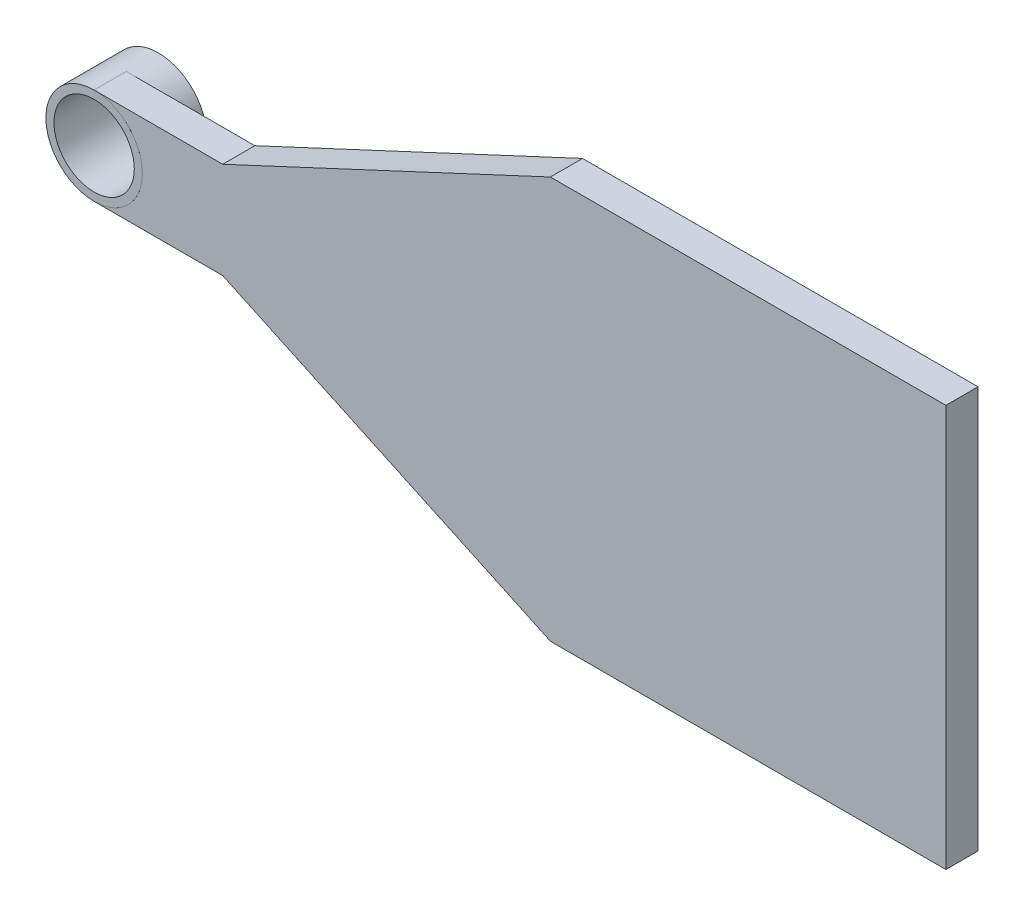
SolidWorks part; units mm, degrees
ref_plane "Front Plane" through (0, 0, 0) normal (0, 0, 1) x (1, 0, 0)
ref_plane "Top Plane" through (0, 0, 0) normal (0, 1, 0) x (1, 0, 0)
ref_plane "Right Plane" through (0, 0, 0) normal (1, 0, 0) x (0, 0, -1)
sketch "Sketch2" plane through (0, 0, 0) normal (0, 0, 1) x (1, 0, 0)
  circle A0 centre (0, 0) radius 5
  circle A1 centre (0, 0) radius 6
  dimension "D1" = 10
extrude "Boss-Extrude1" add sketch "Sketch2" along normal blind 8
ref_plane "Plane1" through (6, 0, 0) normal (1, 0, 0) x (0, 0, -1)
sketch "Sketch3" plane through (6, 0, 0) normal (1, 0, 0) x (0, 0, -1)
  line L0 (-8, 6) -> (-8, -6) construction
  line L5 (-4, -6) -> (-8, -6)
  line L6 (-8, -6) -> (-8, 6)
  line L7 (-4, -6) -> (-4, 6)
  line L8 (-8, -6) -> (0, -6) construction
  line L10 (-8, 6) -> (-4, 6)
  point P0 (-8, 0)
extrude "Boss-Extrude2" add sketch "Sketch3" along normal blind 10 and the other way up to surface separate body
sketch "Sketch4" plane through (0, 0, 4) normal (0, 0, -1) x (-1, 0, 0)
  line L0 (-16, 6) -> (-56.7839, 25.0178)
  line L1 (-16, -6) -> (-56.7839, -25.0178)
  line L2 (-16, 6) -> (-16, -6)
  line L6 (-106, -25.0178) -> (-56.7839, -25.0178)
  line L7 (-56.7839, 25.0178) -> (-106, 25.0178)
  line L8 (-106, 25.0178) -> (-106, -25.0178)
extrude "Boss-Extrude3" add sketch "Sketch4" against normal up to surface (4 mm away) up to face at (9.5, 0, 8)
